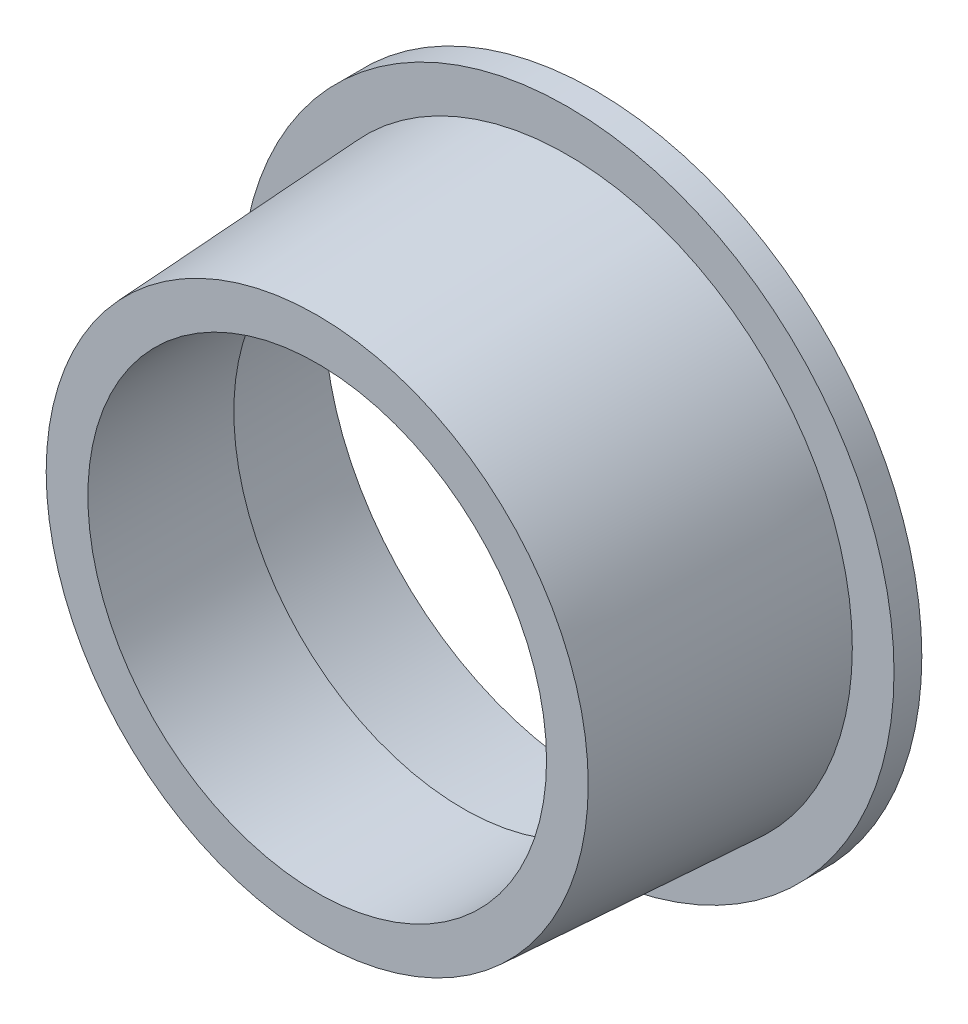
SolidWorks part; units mm, degrees
ref_plane "Front Plane" through (0, 0, 0) normal (1, 0, 0) x (0, 1, 0)
ref_plane "Top Plane" through (0, 0, 0) normal (0, 0, 1) x (0, 1, 0)
ref_plane "Right Plane" through (0, 0, 0) normal (0, 1, 0) x (-1, 0, 0)
sketch "Sketch1" plane through (0, 0, 0) normal (0, 1, 0) x (-1, 0, 0)
  line L0 (19.5, 0) -> (19.25, 8)
  line L1 (19.25, 8) -> (16.5, 9.5)
  line L2 (16.5, 9.5) -> (16.5, 20)
  line L3 (16.5, 20) -> (0, 20) construction
  line L4 (0, 20) -> (0, 0) construction
  line L5 (0, 0) -> (19.5, 0) construction
  line L8 (23.5, 0) -> (19.5, 0)
  line L9 (23.5, 0) -> (23.5, 2)
  line L10 (23.5, 2) -> (20.5, 2)
  line L11 (20.5, 2) -> (19.5, 20)
  line L12 (19.5, 20) -> (16.5, 20)
  dimension "D1" = 19.5
  dimension "D2" = 8
  dimension "D3" = 19.25
  dimension "D4" = 16.5
  dimension "D5" = 9.5
  dimension "D6" = 20
  dimension "D7" = 16.5
  dimension "D8" = 4
  dimension "D9" = 2
  dimension "D10" = 20.5
  dimension "D11" = 19.5
revolve "Revolve1" add sketch "Sketch1" angle 360 about L4
